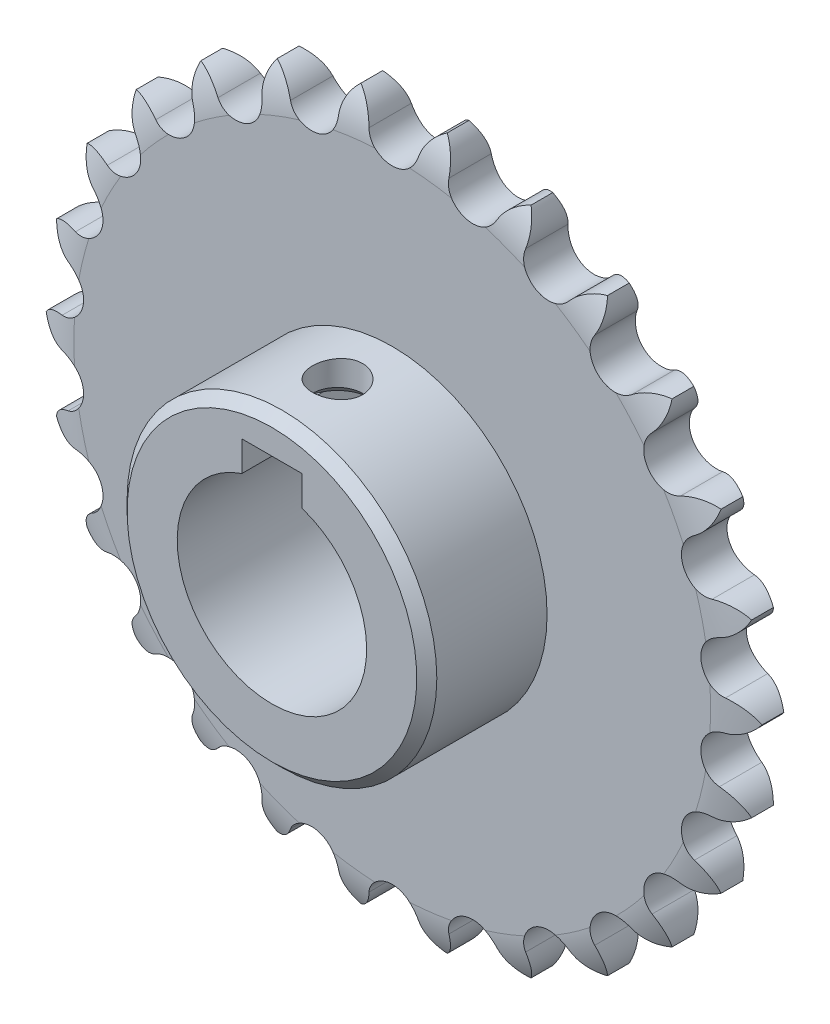
SolidWorks part; units mm, degrees
material "Plain Carbon Steel"
ref_plane "Front Plane" through (0, 0, 0) normal (0, 0, 1) x (1, 0, 0)
ref_plane "Top Plane" through (0, 0, 0) normal (0, 1, 0) x (1, 0, 0)
ref_plane "Right Plane" through (0, 0, 0) normal (1, 0, 0) x (0, 0, -1)
sketch "Sketch1" plane through (0, 0, 0) normal (0, 0, 1) x (1, 0, 0)
  line L0 (0, 0) -> (0, 56.7055) construction
  line L1 (0, 0) -> (9.6217, 51.1475) construction
  circle A0 centre (0, 0) radius 56.7055 construction
  circle A1 centre (0, 0) radius 53.2892 construction
  circle A2 centre (0, 0) radius 52.0446 construction
  arc A3 (-3.9297, 52.4145) -> (3.9297, 52.4145) centre (0, 53.2892) ccw
  arc A4 (6.8687, 56.288) -> (3.9297, 52.4145) centre (9.6217, 51.1475) ccw
  arc A5 (-6.8687, 56.288) -> (-3.9297, 52.4145) centre (-9.6217, 51.1475) cw
  arc A6 (6.8015, 56.2961) -> (8.7281, 51.8318) centre (2.8983, 51.9638) cw
  arc A7 (8.7281, 51.8318) -> (16.3591, 49.951) centre (12.7529, 51.7407) ccw
  arc A8 (20.1397, 53.0086) -> (16.3591, 49.951) centre (21.5825, 47.3586) ccw
  arc A9 (20.0764, 53.0326) -> (20.8786, 48.2369) centre (15.2499, 49.7602) cw
  arc A10 (20.8786, 48.2369) -> (27.8378, 44.5845) centre (24.7647, 47.1852) ccw
  arc A11 (32.2402, 46.6485) -> (27.8378, 44.5845) centre (32.289, 40.8174) ccw
  arc A12 (32.1845, 46.6869) -> (31.8158, 41.8387) centre (26.7151, 44.6648) cw
  arc A13 (31.8158, 41.8387) -> (37.6987, 36.6269) centre (35.3373, 39.8875) ccw
  arc A14 (42.4671, 37.5774) -> (37.6987, 36.6269) centre (41.119, 31.9041) ccw
  arc A15 (42.4222, 37.628) -> (40.9039, 33.0089) centre (36.6278, 36.9736) cw
  arc A16 (40.9039, 33.0089) -> (45.3686, 26.5407) centre (43.8562, 30.2717) ccw
  arc A17 (50.2259, 26.3224) -> (45.3686, 26.5407) centre (47.5593, 21.1366) ccw
  arc A18 (50.1945, 26.3823) -> (47.6149, 22.2608) centre (44.4118, 27.1336) cw
  arc A19 (47.6149, 22.2608) -> (50.4019, 14.9121) centre (49.8263, 18.8966) ccw
  arc A20 (55.0658, 13.5376) -> (50.4019, 14.9121) centre (51.2356, 9.1407) ccw
  arc A21 (55.0496, 13.6034) -> (51.5586, 10.2189) centre (49.6148, 15.7167) cw
  arc A22 (51.5586, 10.2189) -> (52.506, 2.4168) centre (52.9007, 6.4233) ccw
  arc A23 (56.7055, -0.0338) -> (52.506, 2.4168) centre (51.9343, -3.3864) ccw
  arc A24 (56.7055, 0.0338) -> (52.506, -2.4168) centre (51.9343, 3.3864) cw
  arc A25 (52.506, -2.4168) -> (51.5586, -10.2189) centre (52.9007, -6.4233) ccw
  arc A26 (55.0496, -13.6034) -> (51.5586, -10.2189) centre (49.6148, -15.7167) ccw
  arc A27 (55.0658, -13.5376) -> (50.4019, -14.9121) centre (51.2356, -9.1407) cw
  arc A28 (50.4019, -14.9121) -> (47.6149, -22.2608) centre (49.8263, -18.8966) ccw
  arc A29 (50.1945, -26.3823) -> (47.6149, -22.2608) centre (44.4118, -27.1336) ccw
  arc A30 (50.2259, -26.3224) -> (45.3686, -26.5407) centre (47.5593, -21.1366) cw
  arc A31 (45.3686, -26.5407) -> (40.9039, -33.0089) centre (43.8562, -30.2717) ccw
  arc A32 (42.4222, -37.628) -> (40.9039, -33.0089) centre (36.6278, -36.9736) ccw
  arc A33 (42.4671, -37.5774) -> (37.6987, -36.6269) centre (41.119, -31.9041) cw
  arc A34 (37.6987, -36.6269) -> (31.8158, -41.8387) centre (35.3373, -39.8875) ccw
  arc A35 (32.1845, -46.6869) -> (31.8158, -41.8387) centre (26.7151, -44.6648) ccw
  arc A36 (32.2402, -46.6485) -> (27.8378, -44.5845) centre (32.289, -40.8174) cw
  arc A37 (27.8378, -44.5845) -> (20.8786, -48.2369) centre (24.7647, -47.1852) ccw
  arc A38 (20.0764, -53.0326) -> (20.8786, -48.2369) centre (15.2499, -49.7602) ccw
  arc A39 (20.1397, -53.0086) -> (16.3591, -49.951) centre (21.5825, -47.3586) cw
  arc A40 (16.3591, -49.951) -> (8.7281, -51.8318) centre (12.7529, -51.7407) ccw
  arc A41 (6.8015, -56.2961) -> (8.7281, -51.8318) centre (2.8983, -51.9638) ccw
  arc A42 (6.8687, -56.288) -> (3.9297, -52.4145) centre (9.6217, -51.1475) cw
  arc A43 (3.9297, -52.4145) -> (-3.9297, -52.4145) centre (0, -53.2892) ccw
  arc A44 (-6.8687, -56.288) -> (-3.9297, -52.4145) centre (-9.6217, -51.1475) ccw
  arc A45 (-6.8015, -56.2961) -> (-8.7281, -51.8318) centre (-2.8983, -51.9638) cw
  arc A46 (-8.7281, -51.8318) -> (-16.3591, -49.951) centre (-12.7529, -51.7407) ccw
  arc A47 (-20.1397, -53.0086) -> (-16.3591, -49.951) centre (-21.5825, -47.3586) ccw
  arc A48 (-20.0764, -53.0326) -> (-20.8786, -48.2369) centre (-15.2499, -49.7602) cw
  arc A49 (-20.8786, -48.2369) -> (-27.8378, -44.5845) centre (-24.7647, -47.1852) ccw
  arc A50 (-32.2402, -46.6485) -> (-27.8378, -44.5845) centre (-32.289, -40.8174) ccw
  arc A51 (-32.1845, -46.6869) -> (-31.8158, -41.8387) centre (-26.7151, -44.6648) cw
  arc A52 (-31.8158, -41.8387) -> (-37.6987, -36.6269) centre (-35.3373, -39.8875) ccw
  arc A53 (-42.4671, -37.5774) -> (-37.6987, -36.6269) centre (-41.119, -31.9041) ccw
  arc A54 (-42.4222, -37.628) -> (-40.9039, -33.0089) centre (-36.6278, -36.9736) cw
  arc A55 (-40.9039, -33.0089) -> (-45.3686, -26.5407) centre (-43.8562, -30.2717) ccw
  arc A56 (-50.2259, -26.3224) -> (-45.3686, -26.5407) centre (-47.5593, -21.1366) ccw
  arc A57 (-50.1945, -26.3823) -> (-47.6149, -22.2608) centre (-44.4118, -27.1336) cw
  arc A58 (-47.6149, -22.2608) -> (-50.4019, -14.9121) centre (-49.8263, -18.8966) ccw
  arc A59 (-55.0658, -13.5376) -> (-50.4019, -14.9121) centre (-51.2356, -9.1407) ccw
  arc A60 (-55.0496, -13.6034) -> (-51.5586, -10.2189) centre (-49.6148, -15.7167) cw
  arc A61 (-51.5586, -10.2189) -> (-52.506, -2.4168) centre (-52.9007, -6.4233) ccw
  arc A62 (-56.7055, 0.0338) -> (-52.506, -2.4168) centre (-51.9343, 3.3864) ccw
  arc A63 (-56.7055, -0.0338) -> (-52.506, 2.4168) centre (-51.9343, -3.3864) cw
  arc A64 (-52.506, 2.4168) -> (-51.5586, 10.2189) centre (-52.9007, 6.4233) ccw
  arc A65 (-55.0496, 13.6034) -> (-51.5586, 10.2189) centre (-49.6148, 15.7167) ccw
  arc A66 (-55.0658, 13.5376) -> (-50.4019, 14.9121) centre (-51.2356, 9.1407) cw
  arc A67 (-50.4019, 14.9121) -> (-47.6149, 22.2608) centre (-49.8263, 18.8966) ccw
  arc A68 (-50.1945, 26.3823) -> (-47.6149, 22.2608) centre (-44.4118, 27.1336) ccw
  arc A69 (-50.2259, 26.3224) -> (-45.3686, 26.5407) centre (-47.5593, 21.1366) cw
  arc A70 (-45.3686, 26.5407) -> (-40.9039, 33.0089) centre (-43.8562, 30.2717) ccw
  arc A71 (-42.4222, 37.628) -> (-40.9039, 33.0089) centre (-36.6278, 36.9736) ccw
  arc A72 (-42.4671, 37.5774) -> (-37.6987, 36.6269) centre (-41.119, 31.9041) cw
  arc A73 (-37.6987, 36.6269) -> (-31.8158, 41.8387) centre (-35.3373, 39.8875) ccw
  arc A74 (-32.1845, 46.6869) -> (-31.8158, 41.8387) centre (-26.7151, 44.6648) ccw
  arc A75 (-32.2402, 46.6485) -> (-27.8378, 44.5845) centre (-32.289, 40.8174) cw
  arc A76 (-27.8378, 44.5845) -> (-20.8786, 48.2369) centre (-24.7647, 47.1852) ccw
  arc A77 (-20.0764, 53.0326) -> (-20.8786, 48.2369) centre (-15.2499, 49.7602) ccw
  arc A78 (-20.1397, 53.0086) -> (-16.3591, 49.951) centre (-21.5825, 47.3586) cw
  arc A79 (-16.3591, 49.951) -> (-8.7281, 51.8318) centre (-12.7529, 51.7407) ccw
  arc A80 (-6.8015, 56.2961) -> (-8.7281, 51.8318) centre (-2.8983, 51.9638) ccw
  circle A81 centre (0, 0) radius 15
  point P191 (0, 0)
  dimension "D1" = 113.411
  dimension "D2" = 106.5784
  dimension "D3" = 104.0892
  dimension "D4" = 8.0518
  dimension "D5" = 11.6625
  dimension "D7" = 30
  dimension "D6" = 26
extrude "Boss-Extrude1" add sketch "Sketch1" along normal blind 7.2136 contours A5 A80 A79 A78 A77 A76 A75 A74 A73 A72 A71 A70 A69 A68 A67 A66 A65 A64 A63 A62 A61 A60 A59 A58 A57 A56 A55 A54 A53 A52 A51 A50 A49 A48 A47 A46 A45 A44 A43 A42 A41 A40 A39 A38 A37 A36 A35 A34 A33 A32 A31
sketch "Sketch2" plane through (0, 0, 0) normal (1, 0, 0) x (0, 0, -1)
  line L0 (0, 0) -> (-7.2136, 0) construction
  line L1 (-7.2136, 0) -> (-41.868, 0) construction
  line L2 (-7.2136, 15) -> (-38.0802, 15) construction
  line L3 (-7.2136, 15) -> (-26.2636, 15)
  line L4 (-7.2136, 15) -> (-7.2136, 24.525)
  line L5 (-7.2136, 24.525) -> (-26.2636, 24.525)
  line L6 (-26.2636, 15) -> (-26.2636, 24.525)
  dimension "D1" = 19.05
  dimension "D2" = 24.525
  dimension "D3" = 15
revolve "Revolve1" add sketch "Sketch2" angle 360 about L1
sketch "Sketch3" plane through (0, 0, 26.2636) normal (0, 0, 1) x (1, 0, 0)
  line L0 (0, 0) -> (0, 24.525) construction
  line L2 (4.7625, 18.9864) -> (-4.7625, 18.9864)
  line L3 (4.7625, 18.9864) -> (4.7625, 14.2239)
  line L4 (4.7625, 14.2239) -> (-4.7625, 14.2239)
  line L5 (-4.7625, 18.9864) -> (-4.7625, 14.2239)
  circle A0 centre (0, 0) radius 24.525 construction
  circle A1 centre (0, 0) radius 15 construction
  dimension "D1" = 9.525
  dimension "D2" = 4.7625
extrude "Cut-Extrude1" cut sketch "Sketch3" against normal through all
hole_wizard "3/8-16 Tapped Hole1" positions "Sketch5" profile "Sketch4" tap size "3/8-16" standard "ANSI Inch"
sketch "Sketch5" plane through (0, 18.9864, 0) normal (0, -1, 0) x (-1, 0, 0)
  point P0 (0, -15.875)
  dimension "D1" = 15.875
sketch "Sketch4" plane through (0, 18.9864, 15.875) normal (1, 0, 0) x (0, 0, -1)
  line L0 (0, 0) -> (0, 9.4967)
  line L1 (0, 9.4967) -> (3.9687, 7.112)
  line L2 (3.9687, 7.112) -> (3.9687, 1.4288)
  line L3 (3.9687, 1.4288) -> (5.3975, 0)
  line L5 (5.3975, 0) -> (0, 0)
  line L6 (-3.9687, 1.4288) -> (-5.3975, 0) construction
  line L10 (0, 9.4967) -> (-3.9687, 7.112) construction
  line L11 (0, -6.35) -> (0, 107.95) construction
  dimension "Tap Drill Dia." = 7.9375
  dimension "Tap Drill Depth" = 7.112
  dimension "Near C'Sink Dia." = 10.795
  dimension "Near C'Sink Angle" = 90
  dimension "Drill Angle" = 118
cosmetic thread "Hole Thread1" parameters "D1"=19.05, "D2"=9.525
sketch "Sketch6" plane through (0, 0, 0) normal (1, 0, 0) x (0, 0, -1)
  line L0 (-3.6068, 56.2683) -> (-3.6068, 43.2781) construction
  line L1 (-7.2136, 56.2683) -> (0, 56.2683) construction
  line L2 (-5.1943, 56.896) -> (-5.1943, 44.6836) construction
  line L3 (-7.2136, 50.419) -> (-8.8658, 50.419)
  line L4 (-7.2136, 52.9981) -> (-7.2136, 48.2369) construction
  line L5 (-8.8658, 50.419) -> (-8.8658, 56.896)
  line L6 (-8.8658, 56.896) -> (-5.1943, 56.896)
  line L7 (0, 0) -> (-88.6499, 0) construction
  line L8 (0, 50.419) -> (1.6522, 50.419)
  line L9 (1.6522, 56.896) -> (-2.0193, 56.896)
  line L10 (1.6522, 50.419) -> (1.6522, 56.896)
  arc A0 (-5.1943, 56.896) -> (-7.2136, 50.419) centre (5.48, 50.0149) ccw
  arc A1 (-2.0193, 56.896) -> (0, 50.419) centre (-12.6936, 50.0149) cw
  dimension "D2" = 12.7
  dimension "D1" = 1.5875
  dimension "D3" = 50.419
  dimension "D4" = 56.896
revolve "Cut-Revolve1" cut sketch "Sketch6" angle 360 about L7
chamfer "Chamfer1" distance 1.5875 angle 45 1 edges at (0, 24.525, 26.2636)
